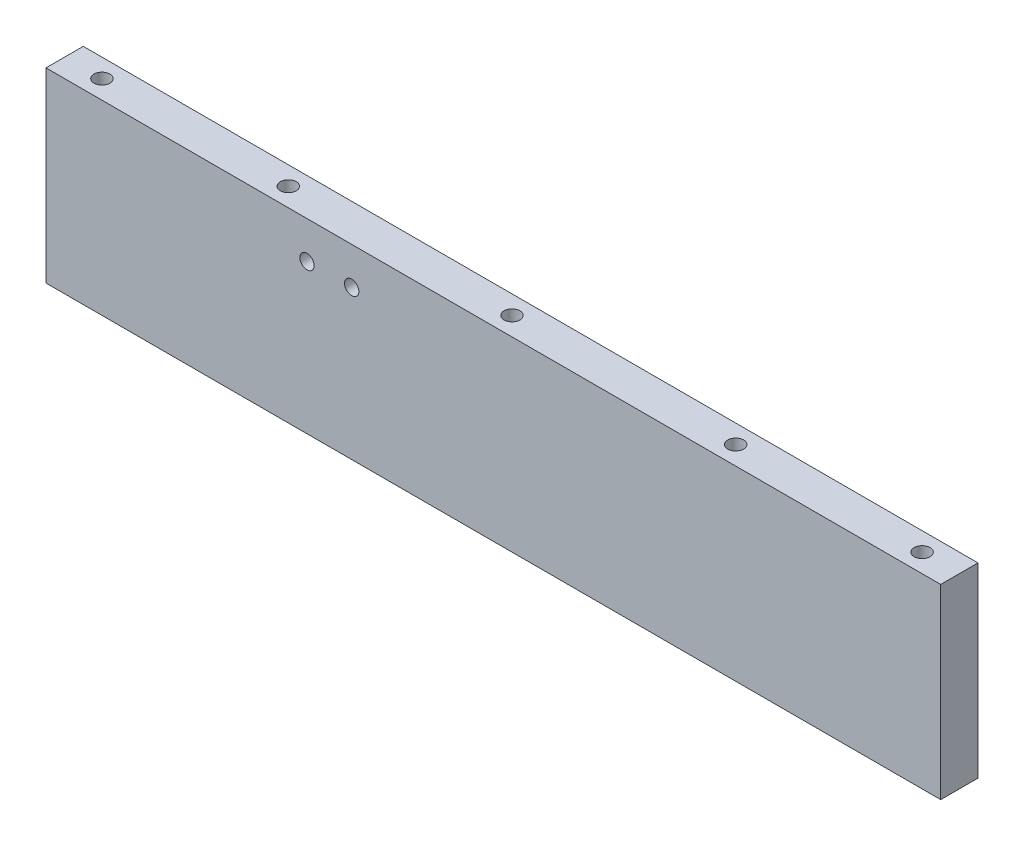
SolidWorks part; units mm, degrees
material "PE High Density"
ref_plane "Front Plane" through (0, 0, 0) normal (0, 0, 1) x (1, 0, 0)
ref_plane "Top Plane" through (0, 0, 0) normal (0, 1, 0) x (1, 0, 0)
ref_plane "Right Plane" through (0, 0, 0) normal (1, 0, 0) x (0, 0, -1)
sketch "Sketch1" plane through (0, 0, 0) normal (0, 0, 1) x (1, 0, 0)
  line L1 (-76.2, -15.875) -> (76.2, -15.875)
  line L2 (-76.2, -15.875) -> (-76.2, 15.875)
  line L3 (-76.2, 15.875) -> (76.2, 15.875)
  line L4 (76.2, -15.875) -> (76.2, 15.875)
  line L5 (-76.2, -15.875) -> (76.2, 15.875) construction
  line L6 (-76.2, 15.875) -> (76.2, -15.875) construction
  point P0 (0, 0)
  dimension "D1" = 152.4
  dimension "D2" = 31.75
extrude "Boss-Extrude1" add sketch "Sketch1" against normal blind 6.35
sketch "Sketch2" plane through (0, 0, 0) normal (0, 0, 1) x (1, 0, 0)
  line L0 (-31.75, 9.525) -> (-24.13, 9.525) construction
  line L1 (76.2, 15.875) -> (-76.2, 15.875) construction
  line L2 (-76.2, 15.875) -> (-76.2, -15.875) construction
  dimension "D1" = 7.62
  dimension "D2" = 6.35
  dimension "D3" = 44.45
hole_wizard "#2 Clearance Hole1" positions "Sketch3" profile "Sketch4" hole size "#2" standard "ANSI Inch" end condition up to next
sketch "Sketch3" plane through (0, 0, 0) normal (0, 0, 1) x (1, 0, 0)
  point P0 (-31.75, 9.525)
  point P3 (-24.13, 9.525)
sketch "Sketch4" plane through (-31.75, 9.525, 0) normal (1, 0, 0) x (0, -1, 0)
  line L0 (0, 0) -> (0, 6.35)
  line L1 (0, 6.35) -> (1.2192, 6.35)
  line L2 (1.2192, 6.35) -> (1.2192, 0)
  line L5 (1.2192, 0) -> (0, 0)
  line L11 (0, -6.35) -> (0, 107.95) construction
  dimension "Thru Hole Dia." = 2.4384
  dimension "Thru Hole Depth" = 6.35
sketch "Sketch5" plane through (0, 15.875, 0) normal (0, 1, 0) x (1, 0, 0)
  line L0 (-76.2, 3.175) -> (76.2, 3.175) construction
  line L1 (-76.2, 6.35) -> (-76.2, 0) construction
  line L2 (76.2, 6.35) -> (76.2, 0) construction
  point P6 (-69.85, 3.175)
  point P7 (-38.1, 3.175)
  point P8 (0, 3.175)
  point P9 (38.1, 3.175)
  point P10 (69.85, 3.175)
  dimension "D1" = 38.1
  dimension "D2" = 38.1
  dimension "D3" = 6.35
  dimension "D4" = 6.35
hole_wizard "Tap Drill for #6-32 Tap1" positions "Sketch6" profile "Sketch7" hole size "#6-32" standard "ANSI Inch"
sketch "Sketch6" plane through (0, 15.875, 0) normal (0, 1, 0) x (1, 0, 0)
  point P0 (-69.85, 3.175)
  point P3 (-38.1, 3.175)
  point P6 (0, 3.175)
  point P9 (38.1, 3.175)
  point P12 (69.85, 3.175)
sketch "Sketch7" plane through (-69.85, 15.875, -3.175) normal (1, 0, 0) x (0, 0, 1)
  line L0 (0, 0) -> (0, 13.5127)
  line L1 (0, 13.5127) -> (1.3525, 12.7)
  line L2 (1.3525, 12.7) -> (1.3525, 0)
  line L5 (1.3525, 0) -> (0, 0)
  line L10 (0, 13.5127) -> (-1.3526, 12.7) construction
  line L11 (0, -6.35) -> (0, 107.95) construction
  dimension "Hole Dia." = 2.7051
  dimension "Hole Depth" = 12.7
  dimension "Drill Angle" = 118
mirror "Mirror1" about plane through (0, 0, 0) normal (0, 1, 0) of "Tap Drill for #6-32 Tap1"
